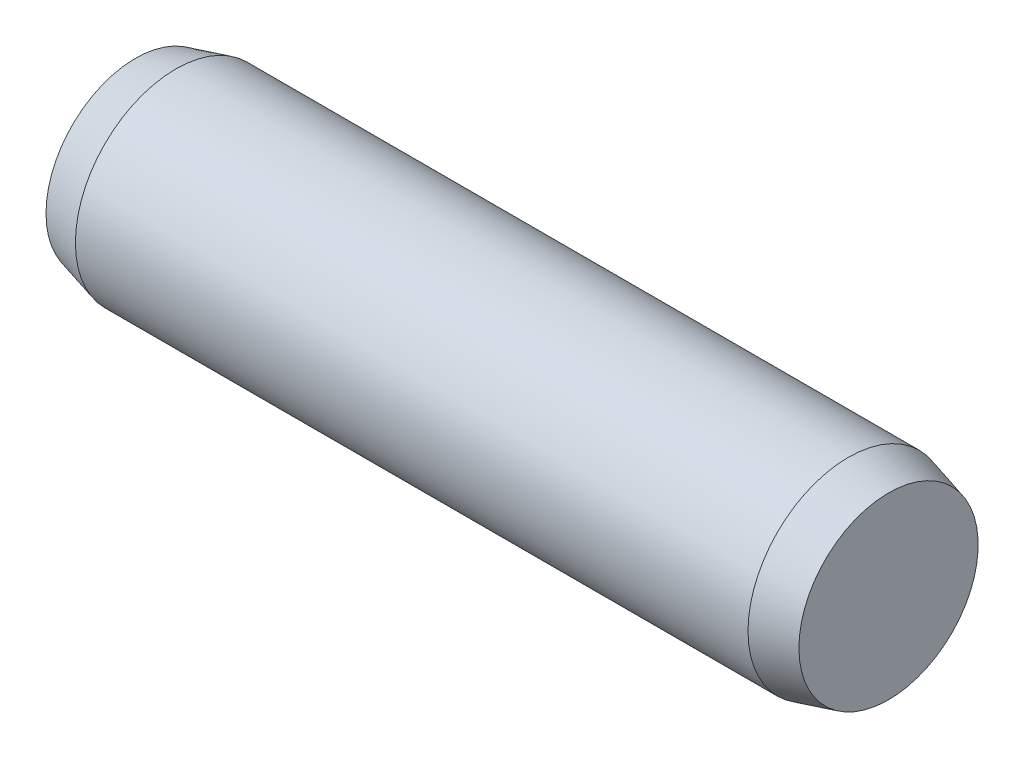
SolidWorks part; units mm, degrees
ref_plane "Front" through (0, 0, 0) normal (0, 0, 1) x (1, 0, 0)
ref_plane "Top" through (0, 0, 0) normal (0, 1, 0) x (1, 0, 0)
ref_plane "Right" through (0, 0, 0) normal (1, 0, 0) x (0, 0, -1)
other "Configuration Table"
sketch "Sketch1" plane through (0, 0, 0) normal (0, 0, 1) x (1, 0, 0)
  line L0 (0, 0) -> (30, 0)
  line L1 (30, 0) -> (30, 3.5713)
  line L2 (30, 3.5713) -> (28.4, 4)
  line L3 (28.4, 4) -> (1.6, 4)
  line L4 (1.6, 4) -> (0, 3.5713)
  line L5 (0, 3.5713) -> (0, 0)
  line L6 (-6.9767, 0) -> (2.6973, 0) construction
  dimension "l" = 30
  dimension "D2" = 15
  dimension "D3" = 15
  dimension "d" = 8
  dimension "c" = 1.6
  dimension "D6" = 1.6
revolve "Base-Revolve" add sketch "Sketch1" angle 360 about L6
equation "\"D6@Sketch1\" = \"c@Sketch1\""
